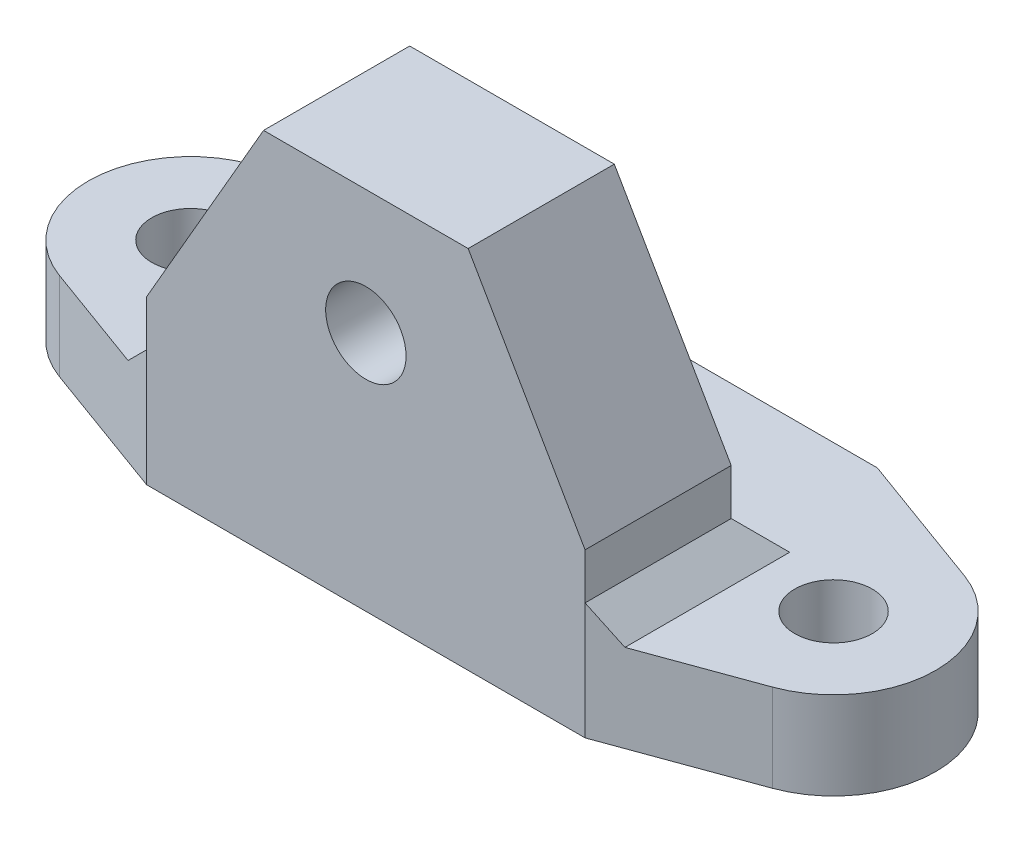
SolidWorks part; units mm, degrees
ref_plane "Front Plane" through (0, 0, 0) normal (0, 0, 1) x (1, 0, 0)
ref_plane "Top Plane" through (0, 0, 0) normal (0, 1, 0) x (1, 0, 0)
ref_plane "Right Plane" through (0, 0, 0) normal (1, 0, 0) x (0, 0, -1)
sketch "Sketch1" plane through (0, 0, 0) normal (0, 0, 1) x (1, 0, 0)
  line L1 (-15, 12.5) -> (15, 12.5)
  line L2 (-15, 12.5) -> (-15, -12.5)
  line L3 (-15, -12.5) -> (15, -12.5)
  line L4 (15, 12.5) -> (15, -12.5)
  line L5 (-15, 12.5) -> (15, -12.5) construction
  line L6 (-15, -12.5) -> (15, 12.5) construction
  point P0 (0, 0)
  dimension "D1" = 25
  dimension "D2" = 30
extrude "Boss-Extrude1" add sketch "Sketch1" along normal blind 20
sketch "Sketch2" plane through (0, 0, 0) normal (0, 0, 1) x (1, 0, 0)
  line L2 (0, -11) -> (0, 11) construction
  line L3 (11, 0) -> (-11, 0) construction
  circle A0 centre (0, 4) radius 5.25
  dimension "D1" = 10.5
  dimension "D2" = 4
extrude "Cut-Extrude1" cut sketch "Sketch2" along normal blind 15
sketch "Sketch3" plane through (0, 0, 0) normal (0, 0, 1) x (1, 0, 0)
  line L0 (11, 0) -> (-11, 0) construction
  line L1 (0, -11) -> (0, 11) construction
  circle A0 centre (0, 4) radius 2.75
  dimension "D1" = 5.5
  dimension "D2" = 4
extrude "Cut-Extrude2" cut sketch "Sketch3" along normal up to next
sketch "Sketch4" plane through (0, -12.5, 0) normal (0, -1, 0) x (1, 0, 0)
  line L0 (-22, 10) -> (34.0128, 10) construction
  line L1 (13.75, 0) -> (-13.75, 0) construction
  line L2 (0, -1.0234) -> (0, 38.56) construction
  line L3 (0, -13.75) -> (0, 13.75) construction
  line L4 (-15, 20) -> (-24.396, 16.5772)
  line L5 (-15, 0) -> (-24.396, 3.4228)
  line L6 (-15, 20) -> (-15, 0) construction
  line L7 (15, 0) -> (24.396, 3.4228)
  line L8 (15, 20) -> (24.396, 16.5772)
  line L9 (-15, 20) -> (-15, 0)
  line L10 (15, 20) -> (15, 0)
  arc A0 (-24.396, 16.5772) -> (-24.396, 3.4228) centre (-22, 10) ccw
  circle A1 centre (-22, 10) radius 2.65
  circle A2 centre (22, 10) radius 2.65
  arc A3 (24.396, 16.5772) -> (24.396, 3.4228) centre (22, 10) cw
  dimension "D3" = 7
  dimension "D4" = 5.3
  dimension "D1" = 10
  dimension "D2" = 22
extrude "Boss-Extrude2" add sketch "Sketch4" against normal blind 6
chamfer "Chamfer1" distance 8 angle 60 2 edges at (-15, 12.5, 10) (15, 12.5, 10)
sketch "Sketch5" plane through (0, 0, 0) normal (1, 0, 0) x (0, 0, -1)
  line L0 (-20, 12.5) -> (0, 12.5) construction
  line L1 (-10, 12.5) -> (0, 12.5)
  line L2 (-10, 12.5) -> (-10, -6.5)
  line L3 (-10, -6.5) -> (0, -6.5)
  line L4 (0, 12.5) -> (0, -6.5)
  line L5 (0, 13.75) -> (0, -13.75) construction
  line L7 (0, -6.5) -> (-3.4228, -6.5) construction
  dimension "D1" = 10
extrude "Cut-Extrude3" cut sketch "Sketch5" against normal mid plane 40
chamfer "Chamfer2" distance 2 angle 45 3 edges at (0, -6.5, 10)
